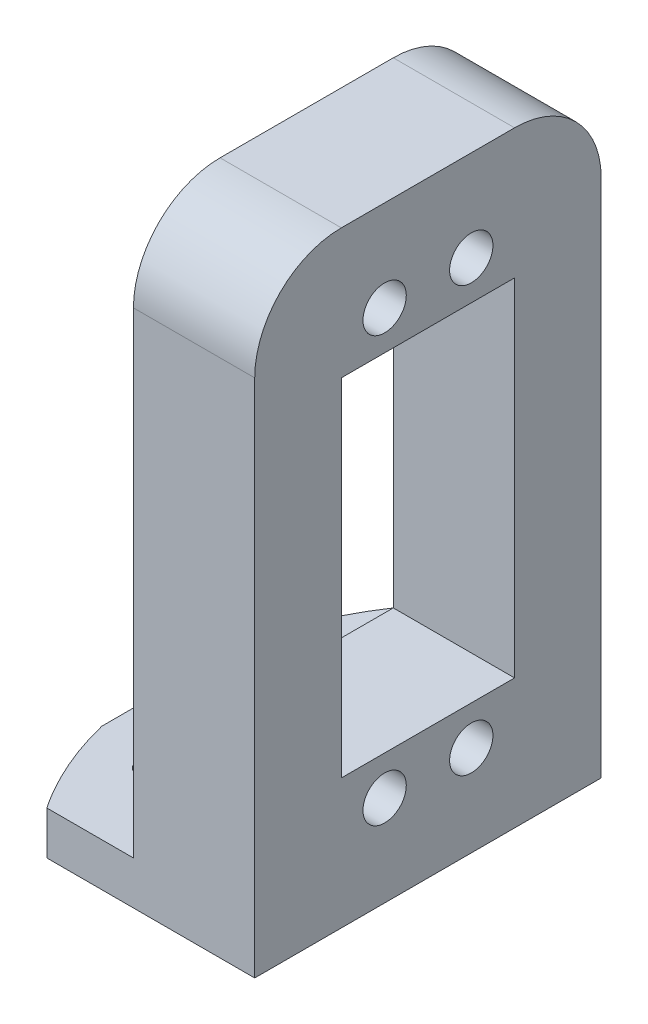
SolidWorks part; units mm, degrees
ref_plane "Front Plane" through (0, 0, 0) normal (0, 0, 1) x (1, 0, 0)
ref_plane "Top Plane" through (0, 0, 0) normal (0, 1, 0) x (1, 0, 0)
ref_plane "Right Plane" through (0, 0, 0) normal (1, 0, 0) x (0, 0, -1)
sketch "Sketch1" plane through (0, 0, 0) normal (1, 0, 0) x (0, 0, -1)
  line L1 (-20, 35) -> (20, 35)
  line L2 (-20, 35) -> (-20, -35)
  line L3 (-20, -35) -> (20, -35)
  line L4 (20, 35) -> (20, -35)
  line L5 (-20, 35) -> (20, -35) construction
  line L6 (-20, -35) -> (20, 35) construction
  point P0 (0, 0)
  dimension "D1" = 40
  dimension "D2" = 70
extrude "Boss-Extrude2" add sketch "Sketch1" along normal blind 9
sketch "Sketch3" plane through (0, 0, 0) normal (-1, 0, 0) x (0, 0, 1)
  line L1 (-10, 20) -> (10, 20)
  line L2 (-10, 20) -> (-10, -20)
  line L3 (-10, -20) -> (10, -20)
  line L4 (10, 20) -> (10, -20)
  line L5 (-10, 20) -> (10, -20) construction
  line L6 (-10, -20) -> (10, 20) construction
  point P0 (0, 0)
  dimension "D1" = 20
  dimension "D2" = 40
extrude "Cut-Extrude1" cut sketch "Sketch3" against normal through all
sketch "Sketch4" plane through (9, 0, 0) normal (1, 0, 0) x (0, 0, -1)
  line L0 (-20, 35) -> (-20, -35) construction
  line L1 (-10, 20) -> (10, 20) construction
  line L2 (10, -20) -> (-10, -20) construction
  circle A0 centre (-5, -24.5) radius 1.5
  circle A1 centre (5, -24.5) radius 1.5
  circle A2 centre (-5, 24.5) radius 1.5
  circle A3 centre (5, 24.5) radius 1.5
  point P0 (-5, 24.5)
  point P3 (5, 24.5)
  point P6 (-5, -24.5)
  point P7 (5, -24.5)
  dimension "D7" = 3
  dimension "D8" = 3
  dimension "D9" = 3
  dimension "D10" = 3
  dimension "D1" = 15
  dimension "D2" = 10
  dimension "D3" = 4.5
  dimension "D4" = 4.5
  dimension "D5" = 4.5
  dimension "D6" = 4.5
extrude "Cut-Extrude2" cut sketch "Sketch4" against normal through all
sketch "Sketch6" plane through (0, 0, 0) normal (-1, 0, 0) x (0, 0, 1)
  line L0 (20, 35) -> (20, -35) construction
  line L1 (-20, -35) -> (20, -35)
  line L2 (-20, -35) -> (-20, -30)
  line L3 (-20, -30) -> (20, -30)
  line L4 (20, -35) -> (20, -30)
  dimension "D1" = 5
extrude "Boss-Extrude3" add sketch "Sketch6" along normal blind 15
sketch "Sketch7" plane through (9, 0, 0) normal (1, 0, 0) x (0, 0, -1)
  line L0 (-20, 35) -> (-20, -35) construction
  line L1 (20, 35) -> (-20, 35) construction
  line L2 (-20, 25) -> (-20, 35)
  line L3 (-20, 35) -> (-10, 35)
  line L4 (20, -35) -> (20, 35) construction
  line L5 (10, 35) -> (20, 35)
  line L6 (20, 35) -> (20, 25)
  arc A0 (-10, 35) -> (-20, 25) centre (-10, 25) ccw
  arc A1 (20, 25) -> (10, 35) centre (10, 25) ccw
  point P0 (-20, 25)
  point P1 (-10, 35)
  point P8 (10, 35)
  point P12 (20, 25)
  dimension "D1" = 10
  dimension "D2" = 10
  dimension "D3" = 10
  dimension "D4" = 10
extrude "Cut-Extrude3" cut sketch "Sketch7" against normal through all
sketch "Sketch8" plane through (0, 0, -20) normal (0, 0, -1) x (-1, 0, 0)
  line L0 (0, -30) -> (0, 25) construction
  line L1 (15, -30) -> (0, -30) construction
  line L2 (0, -27) -> (5, -30)
  line L3 (0, -27) -> (0, -30)
  line L4 (0, -30) -> (5, -30)
  point P0 (0, -27)
  point P1 (5, -30)
  dimension "D1" = 3
  dimension "D2" = 5
extrude "Boss-Extrude4" add sketch "Sketch8" against normal blind 40
sketch "Sketch9" plane through (-15, 0, 0) normal (-1, 0, 0) x (0, 0, 1)
  line L1 (-20, -30) -> (20, -30)
  line L2 (-20, -30) -> (-20, -35)
  line L3 (-20, -35) -> (20, -35)
  line L4 (20, -30) -> (20, -35)
extrude "Boss-Extrude5" add sketch "Sketch9" along normal blind 5
sketch "Sketch10" plane through (0, -30, 0) normal (0, 1, 0) x (1, 0, 0)
  line L0 (-20, -20) -> (-20, 20) construction
  line L1 (-20, 20) -> (-5, 20) construction
  line L2 (-20, -20) -> (-5, -20) construction
  circle A0 centre (-13, 10) radius 1.5
  circle A1 centre (-13, -10) radius 1.5
  point P0 (-13, 10)
  point P1 (-13, -10)
  dimension "D5" = 3
  dimension "D6" = 3
  dimension "D1" = 7
  dimension "D2" = 7
  dimension "D3" = 10
  dimension "D4" = 10
extrude "Cut-Extrude4" cut sketch "Sketch10" against normal through all
sketch "Sketch11" plane through (0, -30, 0) normal (0, 1, 0) x (1, 0, 0)
  line L0 (-20, 20) -> (-5, 20) construction
  line L1 (-20, -20) -> (-20, 20) construction
  line L2 (-20, -20) -> (-5, -20) construction
  line L5 (-15, 20) -> (-23.0603, 8.003) construction
  line L6 (-23.0603, 8.003) -> (-23.0603, -7.997) construction
  line L8 (-23.0603, -7.997) -> (-15, -20) construction
  line L9 (-15, 20) -> (-20, 20)
  line L10 (-20, 20) -> (-20, -20)
  line L11 (-20, -20) -> (-15, -20)
  spline S0 degree 3 poles (-15, 20) (-23.0603, 8.003) (-23.0603, -7.997) (-15, -20) knots 0 0 0 0 1 1 1 1
  point P0 (-15, 20)
  point P1 (-20, 8)
  point P4 (-15, -20)
  point P7 (-20, -8)
  line M3 (-20, -20) -> (-5, -20)
  line M5 (-5, 20) -> (-20, 20)
  line M6 (-20, 20) -> (-20, -20)
  dimension "D1" = 5
  dimension "D2" = 12
  dimension "D3" = 12
  dimension "D4" = 5
extrude "Cut-Extrude5" cut sketch "Sketch11" against normal through all contours S0 M5 M6 | S0 M6 M3
sketch "Sketch12" plane through (0, 0, 0) normal (-1, 0, 0) x (0, 0, 1)
  line L0 (-20, -27) -> (-20, 25) construction
  line L1 (-10, 35) -> (10, 35)
  line L2 (20, 25) -> (20, -27)
  line L3 (20, -27) -> (-20, -27)
  line L4 (-20, -27) -> (-20, 25)
  line L5 (-10, 20) -> (10, 20)
  line L6 (10, 20) -> (10, -20)
  line L7 (10, -20) -> (-10, -20)
  line L8 (-10, -20) -> (-10, 20)
  arc A0 (-10, 35) -> (-20, 25) centre (-10, 25) ccw construction
  arc A1 (-10, 35) -> (-20, 25) centre (-10, 25) ccw
  arc A2 (20, 25) -> (10, 35) centre (10, 25) ccw
  circle A3 centre (-5, 24.5) radius 1.5
  circle A4 centre (5, 24.5) radius 1.5
  circle A5 centre (5, -24.5) radius 1.5
  circle A6 centre (-5, -24.5) radius 1.5
  spline S0 degree 1 poles (-20, -27) (-20, 25) knots 0 0 1 1
  line M1 (-10, 20) -> (10, 20)
  line M2 (10, 20) -> (10, -20)
  line M3 (10, -20) -> (-10, -20)
  line M4 (-10, -20) -> (-10, 20)
  circle M5 centre (5, -24.5) radius 1.5
  circle M6 centre (-5, 24.5) radius 1.5
  circle M7 centre (5, 24.5) radius 1.5
  circle M8 centre (-5, -24.5) radius 1.5
  line M9 (-20, 25) -> (-20, -27)
  line M10 (-20, -27) -> (20, -27)
  line M11 (20, -27) -> (20, 25)
  arc M12 (20, 25) -> (10, 35) centre (10, 25) ccw
  line M13 (10, 35) -> (-10, 35)
  arc M14 (-10, 35) -> (-20, 25) centre (-10, 25) ccw
extrude "Boss-Extrude6" add sketch "Sketch12" along normal blind 3 contours M14 M9 M10 M11 M12 M13 M6 M8 M7 M5 M4 M1 M2 M3
sketch "Sketch13" plane through (0, 0, -20) normal (0, 0, -1) x (-1, 0, 0)
  line L0 (3, -27) -> (5, -30)
  line L1 (5, -30) -> (0, -27)
  line L2 (0, -27) -> (3, -27)
extrude "Boss-Extrude7" add sketch "Sketch13" against normal blind 40
sketch "Sketch14" plane through (-3, 0, 0) normal (-1, 0, 0) x (0, 0, 1)
  line L0 (-20, -27) -> (20, -27)
  line L1 (20, -27) -> (20, 25)
  line L3 (-20, 25) -> (-20, -27)
  line L4 (-10, 35) -> (10, 35)
  line L5 (10, 20) -> (10, -20) construction
  line L6 (-10, 20) -> (10, 20)
  line L7 (-10, 20) -> (-10, -20)
  line L8 (-10, -20) -> (10, -20)
  line L9 (10, 20) -> (10, -20)
  arc A0 (-10, 35) -> (-20, 25) centre (-10, 25) ccw
  arc A1 (20, 25) -> (10, 35) centre (10, 25) ccw
  circle A2 centre (-5, 24.5) radius 1.5
  circle A3 centre (5, 24.5) radius 1.5
  circle A4 centre (-5, -24.5) radius 1.5
  circle A5 centre (5, -24.5) radius 1.5
extrude "Boss-Extrude8" add sketch "Sketch14" along normal blind 2
sketch "Sketch16" plane through (0, 0, -20) normal (0, 0, -1) x (-1, 0, 0)
  line L0 (5, -27) -> (3, -27)
  line L1 (3, -27) -> (5, -30)
  line L2 (5, -30) -> (5, -27)
extrude "Boss-Extrude9" add sketch "Sketch16" against normal blind 40
sketch "Sketch17" plane through (9, 0, 0) normal (1, 0, 0) x (0, 0, -1)
  circle A0 centre (-5, 24.5) radius 2.5
  circle A1 centre (5, 24.5) radius 2.5
  circle A2 centre (-5, -24.5) radius 2.5
  circle A3 centre (5, -24.5) radius 2.5
  dimension "D1" = 5
  dimension "D2" = 5
  dimension "D3" = 5
  dimension "D4" = 5
extrude "Cut-Extrude6" cut sketch "Sketch17" against normal blind 5
